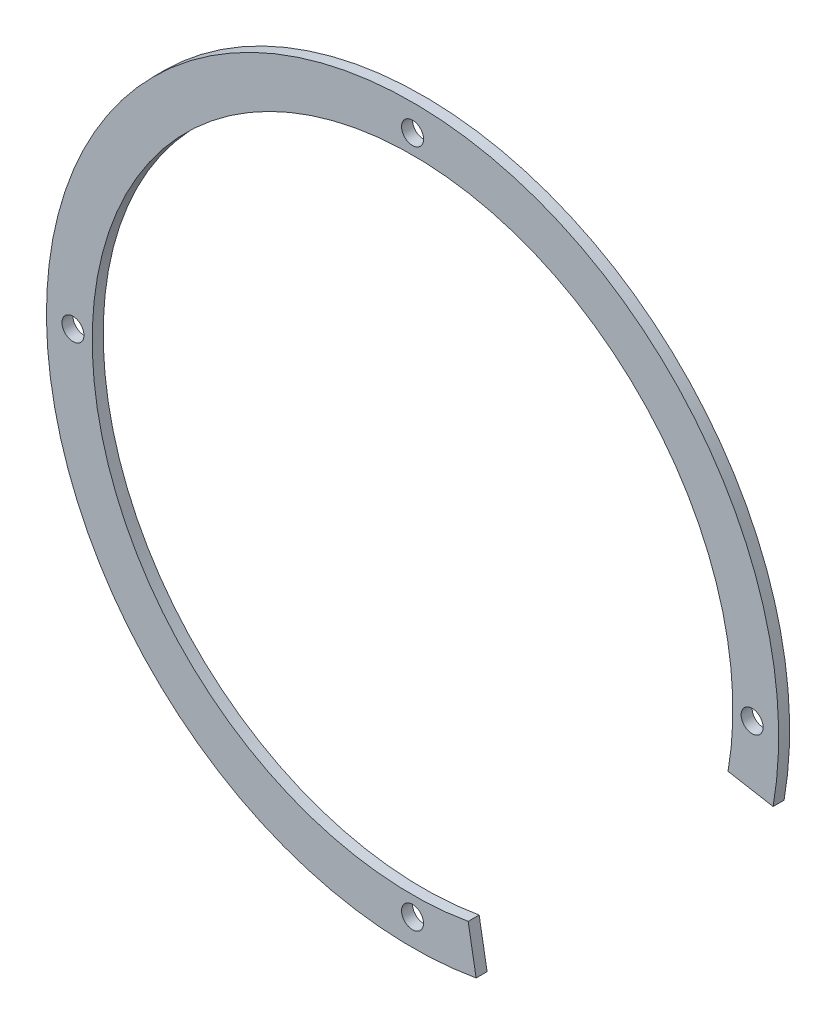
SolidWorks part; units mm, degrees
material "聚脂树脂"
ref_plane "前视基准面" through (0, 0, 0) normal (0, 0, 1) x (1, 0, 0)
ref_plane "上视基准面" through (0, 0, 0) normal (0, 1, 0) x (1, 0, 0)
ref_plane "右视基准面" through (0, 0, 0) normal (1, 0, 0) x (0, 0, -1)
sketch "草图1" plane through (0, 0, 0) normal (0, 0, 1) x (1, 0, 0)
  line L0 (0, 92.75) -> (0, 0) construction
  circle A0 centre (0, 0) radius 100
  circle A1 centre (0, 0) radius 87.5
  circle A3 centre (0, 92.75) radius 3
  circle A4 centre (92.75, 0) radius 3
  circle A5 centre (0, -92.75) radius 3
  circle A6 centre (-92.75, 0) radius 3
  dimension "D1" = 200
  dimension "D2" = 175
  dimension "D4" = 6
  dimension "D3" = 92.75
  dimension "D5" = 4
extrude "凸台-拉伸1" add sketch "草图1" along normal blind 3
sketch "草图2" plane through (0, 0, 3) normal (0, 0, 1) x (1, 0, 0)
  line L0 (0, 0) -> (140.4487, -24.7649) construction
  line L1 (0, 0) -> (21.8984, -124.1918) construction
  line L2 (0, 0) -> (177.7988, 0) construction
  line L3 (15.1942, -86.1707) -> (17.3648, -98.4808)
  line L4 (85.0147, -14.9904) -> (98.4808, -17.3648)
  circle A0 centre (0, 0) radius 87.5 construction
  circle A1 centre (0, 0) radius 100 construction
  arc A2 (15.1942, -86.1707) -> (86.1707, -15.1942) centre (0, 0) ccw
  circle A3 centre (0, 0) radius 100
  arc A4 (17.3648, -98.4808) -> (98.4808, -17.3648) centre (0, 0) ccw
  point P17 (86.1707, -15.1942)
  point P18 (0, 0)
  point P19 (0, 0)
  point P20 (86.1707, -15.1942)
  point P21 (0, 0)
  point P22 (0, 0)
  circle M8 centre (0, 0) radius 100
  circle M9 centre (0, 0) radius 87.5
  dimension "D1" = 10
  dimension "D2" = 80
  dimension "D3" = 0
extrude "切除-拉伸1" cut sketch "草图2" against normal through all contours L4 L3 M9 M8
